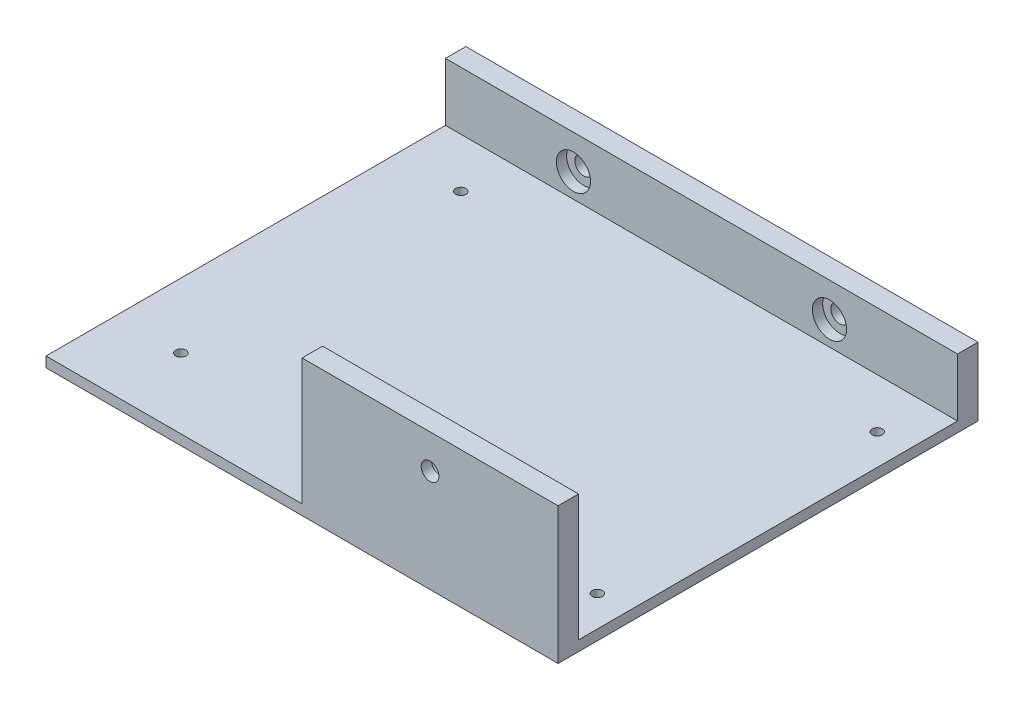
SolidWorks part; units mm, degrees
ref_plane "前视基准面" through (0, 0, 0) normal (0, 0, 1) x (1, 0, 0)
ref_plane "上视基准面" through (0, 0, 0) normal (0, 1, 0) x (1, 0, 0)
ref_plane "右视基准面" through (0, 0, 0) normal (1, 0, 0) x (0, 0, -1)
other "Configuration Table"
sketch "草图1" plane through (0, 0, 0) normal (0, 1, 0) x (1, 0, 0)
  line L1 (0, 0) -> (150, 0)
  line L2 (0, 0) -> (0, 123)
  line L3 (0, 123) -> (150, 123)
  line L4 (150, 0) -> (150, 123)
  line L11 (19, 61.5) -> (19, 102.5)
  line L12 (19, 61.5) -> (19, 20.5)
  line L14 (141, 61.5) -> (141, 102.5)
  line L15 (141, 61.5) -> (141, 20.5)
  circle A0 centre (19, 102.5) radius 1.5
  circle A1 centre (19, 20.5) radius 1.5
  circle A2 centre (141, 20.5) radius 1.5
  circle A3 centre (141, 102.5) radius 1.5
extrude "凸台-拉伸1" add sketch "草图1" along normal blind 3
sketch "草图2" plane through (0, 3, 0) normal (0, 1, 0) x (1, 0, 0)
  line L0 (150, 0) -> (150, 123) construction
  line L1 (0, 123) -> (150, 123)
  line L2 (0, 123) -> (0, 117)
  line L3 (0, 117) -> (150, 117)
  line L4 (150, 123) -> (150, 117)
extrude "凸台-拉伸2" add sketch "草图2" along normal blind 17
sketch "草图3" plane through (0, 3, 0) normal (0, 1, 0) x (1, 0, 0)
  line L1 (150, 0) -> (75, 0)
  line L2 (150, 0) -> (150, 6)
  line L3 (150, 6) -> (75, 6)
  line L4 (75, 0) -> (75, 6)
extrude "凸台-拉伸3" add sketch "草图3" along normal blind 37
sketch "草图4" plane through (0, 0, -6) normal (0, 0, -1) x (-1, 0, 0)
  line L0 (-150, 40) -> (-150, 20)
  line L1 (-150, 20) -> (-75, 40)
  circle A0 centre (-112.5, 30) radius 2.6
extrude "切除-拉伸1" cut sketch "草图4" against normal blind 37 contours L1 A0 | L1 A0
sketch "草图5" plane through (0, 0, -6) normal (0, 0, -1) x (-1, 0, 0)
  circle A0 centre (-112.5, 30) radius 5
extrude "切除-拉伸2" cut sketch "草图5" against normal blind 3
sketch "草图6" plane through (0, 0, -123) normal (0, 0, -1) x (-1, 0, 0)
  line L0 (-150, 20) -> (-150, 0)
  line L2 (0, 20) -> (0, 0) construction
  line L3 (-75, 10) -> (-150, 10)
  line L4 (-75, 10) -> (0, 10)
  circle A0 centre (-112.5, 10) radius 2.6
  circle A1 centre (-37.5, 10) radius 2.6
extrude "切除-拉伸3" cut sketch "草图6" against normal blind 6 contours L3 A0 | L3 A0 | L4 A1 | L4 A1
sketch "草图7" plane through (0, 0, -117) normal (0, 0, 1) x (1, 0, 0)
  circle A0 centre (37.5, 10) radius 5
  circle A1 centre (112.5, 10) radius 5
extrude "切除-拉伸4" cut sketch "草图7" against normal blind 3
